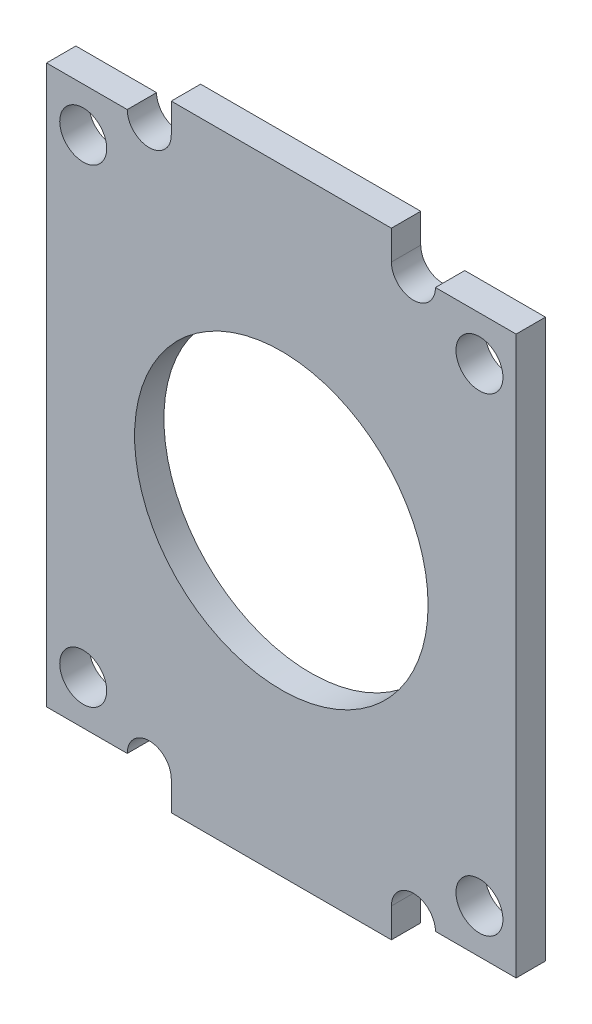
SolidWorks part; units mm, degrees
material "A-玻璃纤维"
ref_plane "前视基准面" through (0, 0, 0) normal (0, 0, 1) x (1, 0, 0)
ref_plane "上视基准面" through (0, 0, 0) normal (0, 1, 0) x (1, 0, 0)
ref_plane "右视基准面" through (0, 0, 0) normal (1, 0, 0) x (0, 0, -1)
sketch "草图1" plane through (0, 0, 0) normal (0, 0, 1) x (1, 0, 0)
  line L1 (-16, 19) -> (16, 19)
  line L2 (-16, 19) -> (-16, -19)
  line L3 (-16, -19) -> (16, -19)
  line L4 (16, 19) -> (16, -19)
  line L5 (0, -19) -> (0, 19) construction
  line L6 (-16, 0) -> (16, 0) construction
  point P0 (0, 0)
  dimension "D1" = 38
  dimension "D2" = 32
extrude "凸台-拉伸1" add sketch "草图1" along normal blind 2
sketch "草图2" plane through (0, 0, 2) normal (0, 0, 1) x (1, 0, 0)
  circle A0 centre (0, 0) radius 10
  dimension "D1" = 20
extrude "切除-拉伸1" cut sketch "草图2" against normal blind 3
sketch "草图3" plane through (0, 0, 2) normal (0, 0, 1) x (1, 0, 0)
  line L0 (16, 19) -> (-16, 19) construction
  line L1 (-7.5, 19) -> (7.5, 19)
  line L2 (-7.5, 19) -> (-7.5, 21)
  line L3 (-7.5, 21) -> (7.5, 21)
  line L4 (7.5, 19) -> (7.5, 21)
  line L5 (-16, -19) -> (16, -19) construction
  line L6 (-7.5, -19) -> (7.5, -19)
  line L7 (-7.5, -19) -> (-7.5, -21)
  line L8 (-7.5, -21) -> (7.5, -21)
  line L9 (7.5, -19) -> (7.5, -21)
  line L10 (-16, 19) -> (-16, -19) construction
  dimension "D1" = 2
  dimension "D2" = 15
  dimension "D3" = 2
  dimension "D4" = 15
  dimension "D5" = 8.5
extrude "凸台-拉伸2" add sketch "草图3" against normal blind 2
sketch "草图4" plane through (0, 0, 2) normal (0, 0, 1) x (1, 0, 0)
  line L0 (-7.5, 19) -> (-16, 19) construction
  line L1 (-16, -19) -> (-7.5, -19) construction
  circle A0 centre (-9, 19) radius 1.5
  circle A1 centre (-9, -19) radius 1.5
  circle A2 centre (9, 19) radius 1.5
  circle A3 centre (9, -19) radius 1.5
  dimension "D1" = 3
  dimension "D2" = 3
extrude "切除-拉伸2" cut sketch "草图4" against normal blind 3
sketch "草图5" plane through (0, 0, 2) normal (0, 0, 1) x (1, 0, 0)
  line L0 (-22.5106, 0) -> (36.1066, 0) construction
  line L1 (16, -19) -> (16, 19) construction
  line L2 (0, 26.1055) -> (0, -26.3163) construction
  circle A0 centre (0, 0) radius 14 construction
  circle A1 centre (13.5, 16) radius 1.6
  circle A2 centre (13.5, -16) radius 1.6
  circle A3 centre (-13.5, -16) radius 1.6
  circle A4 centre (-13.5, 16) radius 1.6
  dimension "D1" = 28
  dimension "D2" = 32
  dimension "D3" = 16
  dimension "D4" = 3.2
  dimension "D5" = 2.5
extrude "切除-拉伸3" cut sketch "草图5" against normal through all
